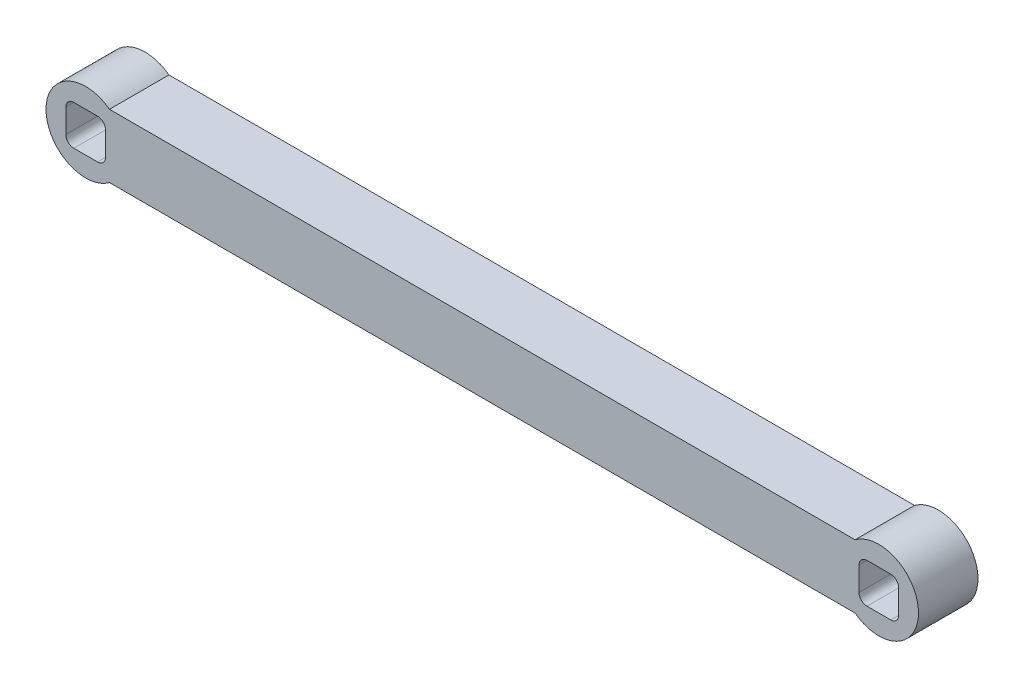
SolidWorks part; units mm, degrees
ref_plane "Front Plane" through (0, 0, 0) normal (0, 0, 1) x (1, 0, 0)
ref_plane "Top Plane" through (0, 0, 0) normal (0, 1, 0) x (1, 0, 0)
ref_plane "Right Plane" through (0, 0, 0) normal (1, 0, 0) x (0, 0, -1)
sketch "Sketch1" plane through (0, 0, 0) normal (0, 0, 1) x (1, 0, 0)
  line L0 (0, 0) -> (-50, 0) construction
  line L1 (-25, 0) -> (-25, 4) construction
  line L6 (0, 0) -> (0, 7.3353) construction
  line L7 (-51.5, -2.5) -> (-48.5, -2.5)
  line L8 (-52.5, -1.5) -> (-52.5, 1.5)
  line L9 (-51.5, 2.5) -> (-48.5, 2.5)
  line L10 (-47.5, -1.5) -> (-47.5, 1.5)
  line L11 (-52.5, -2.5) -> (-47.5, 2.5) construction
  line L12 (-52.5, 2.5) -> (-47.5, -2.5) construction
  line L13 (51.5, 2.5) -> (48.5, 2.5)
  line L14 (47.5, -1.5) -> (47.5, 1.5)
  line L15 (51.5, -2.5) -> (48.5, -2.5)
  line L16 (52.5, -1.5) -> (52.5, 1.5)
  line L17 (-47, -4) -> (47, -4)
  line L18 (47, 4) -> (-47, 4)
  circle A0 centre (0, 0) radius 2.5
  arc A3 (-47, 4) -> (-47, -4) centre (-50, 0) ccw
  arc A4 (-48.5, 2.5) -> (-47.5, 1.5) centre (-48.5, 1.5) cw
  arc A5 (-48.5, -2.5) -> (-47.5, -1.5) centre (-48.5, -1.5) ccw
  arc A6 (-51.5, -2.5) -> (-52.5, -1.5) centre (-51.5, -1.5) cw
  arc A7 (-52.5, 1.5) -> (-51.5, 2.5) centre (-51.5, 1.5) cw
  arc A8 (48.5, 2.5) -> (47.5, 1.5) centre (48.5, 1.5) ccw
  arc A9 (48.5, -2.5) -> (47.5, -1.5) centre (48.5, -1.5) cw
  arc A10 (51.5, -2.5) -> (52.5, -1.5) centre (51.5, -1.5) ccw
  arc A11 (52.5, 1.5) -> (51.5, 2.5) centre (51.5, 1.5) ccw
  arc A12 (47, 4) -> (47, -4) centre (50, 0) cw
  dimension "D1" = 5
  dimension "D3" = 50
  dimension "D4" = 1
  dimension "D5" = 10
  dimension "D6" = 4
  dimension "D7" = 5
  dimension "D8" = 5
extrude "Boss-Extrude1" add sketch "Sketch1" along normal blind 7.5 contours A0 | A12 L18 A3 L17 A11 L16 A10 L15 A9 L14 A8 L13 A0 L8 A7 L9 A4 L10 A5 L7 A6
